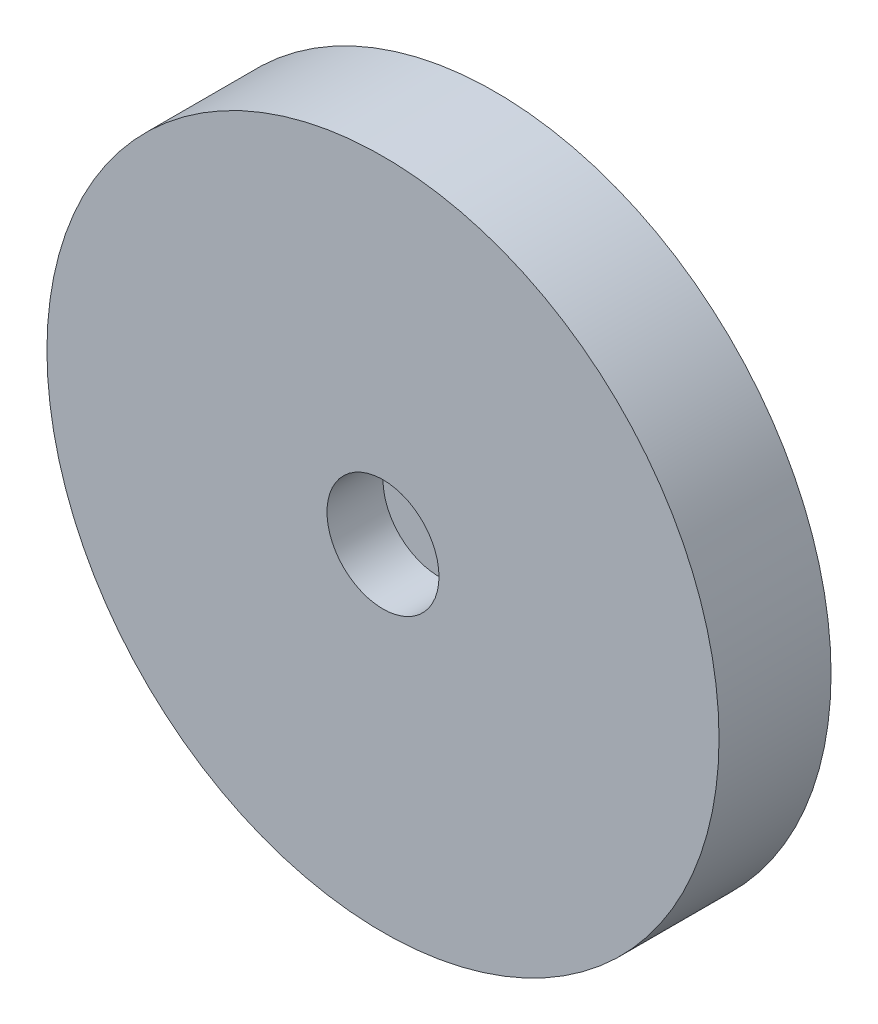
SolidWorks part; units mm, degrees
ref_plane "Front Plane" through (0, 0, 0) normal (0, 0, 1) x (1, 0, 0)
ref_plane "Top Plane" through (0, 0, 0) normal (0, 1, 0) x (1, 0, 0)
ref_plane "Right Plane" through (0, 0, 0) normal (1, 0, 0) x (0, 0, -1)
sketch "Sketch1" plane through (0, 0, 0) normal (0, 0, 1) x (1, 0, 0)
  circle A0 centre (0, 0) radius 150
  dimension "D1" = 300
extrude "Boss-Extrude1" add sketch "Sketch1" along normal blind 50
sketch "Sketch2" plane through (0, 0, 50) normal (0, 0, 1) x (1, 0, 0)
  circle A0 centre (0, 0) radius 25
  dimension "D1" = 50
extrude "Cut-Extrude1" cut sketch "Sketch2" against normal blind 25
